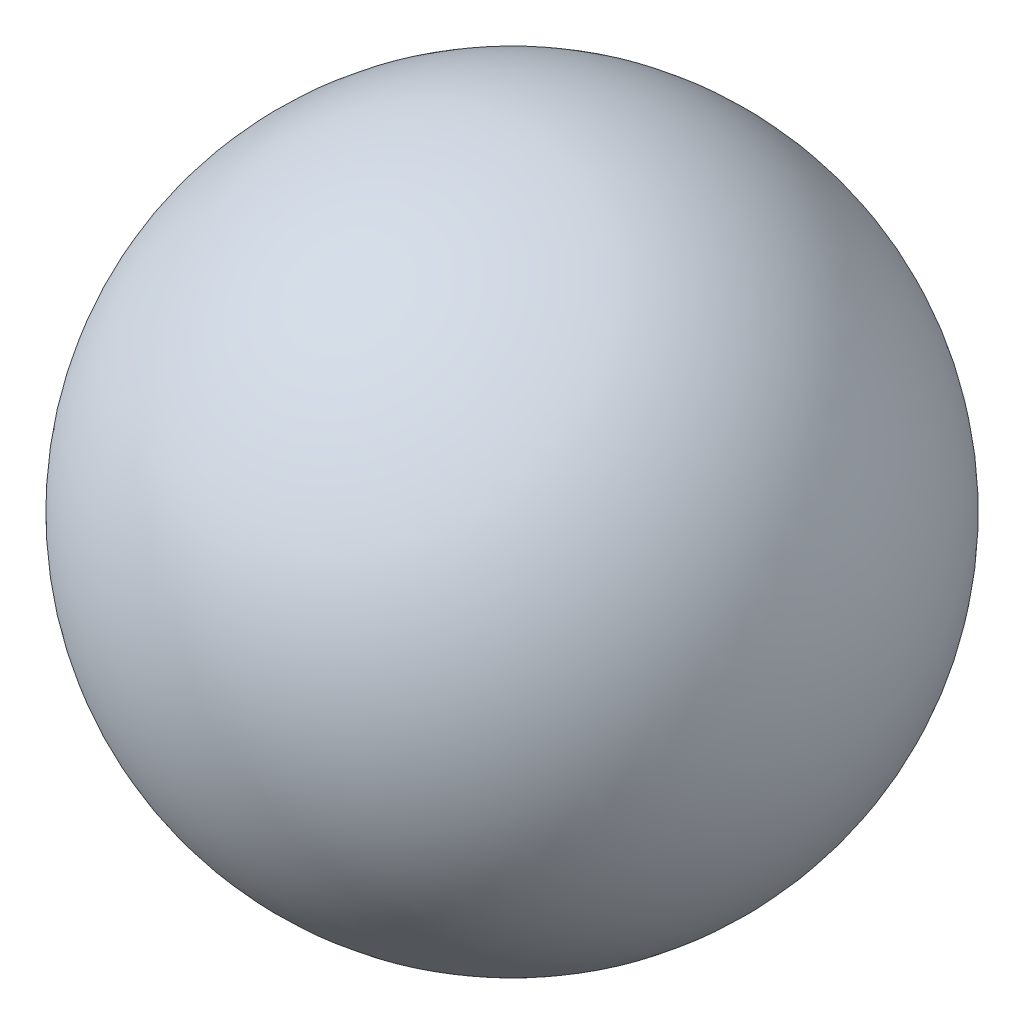
SolidWorks part; units mm, degrees
material "AISI 1020"
ref_plane "Front Plane" through (0, 0, 0) normal (0, 0, 1) x (1, 0, 0)
ref_plane "Top Plane" through (0, 0, 0) normal (0, 1, 0) x (1, 0, 0)
ref_plane "Right Plane" through (0, 0, 0) normal (1, 0, 0) x (0, 0, -1)
sketch "Sketch1" plane through (0, 0, 0) normal (0, 0, 1) x (1, 0, 0)
  line L0 (0, 40) -> (0, -40)
  arc A0 (0, 40) -> (0, -40) centre (0, 0) cw
  dimension "D1" = 40
revolve "Revolve1" add sketch "Sketch1" angle 360 about L0
